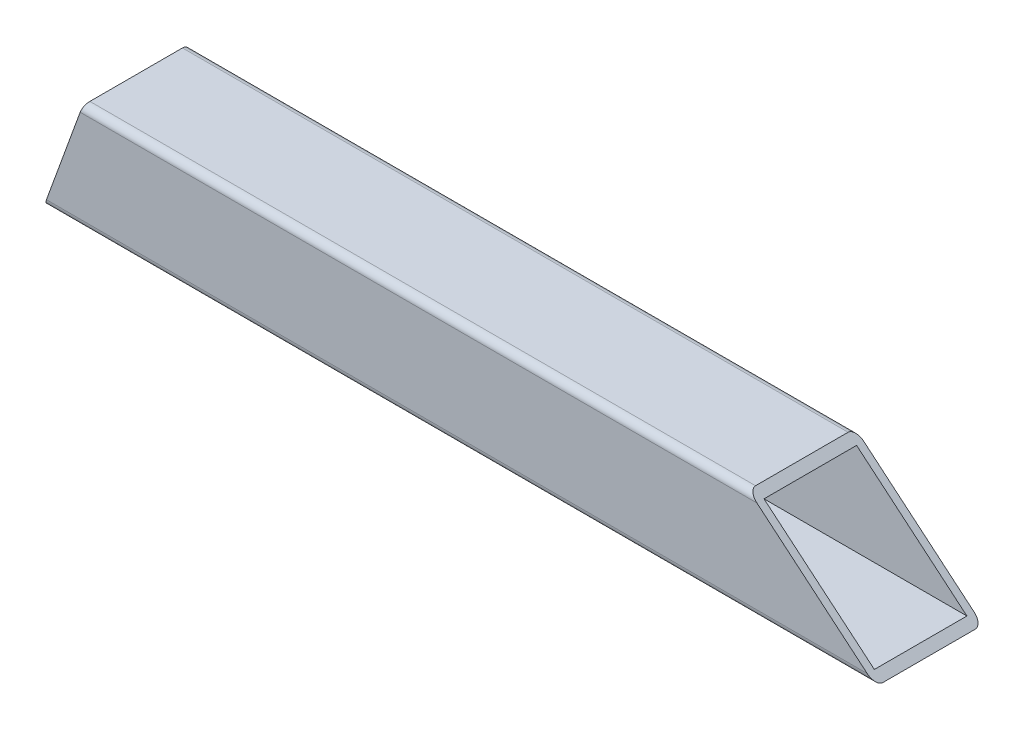
SolidWorks part; units mm, degrees
ref_plane "Front Plane" through (0, 0, 0) normal (0, 0, 1) x (1, 0, 0)
ref_plane "Top Plane" through (0, 0, 0) normal (0, 1, 0) x (1, 0, 0)
ref_plane "Right Plane" through (0, 0, 0) normal (1, 0, 0) x (0, 0, -1)
sketch "Sketch1" plane through (0, 0, 0) normal (1, 0, 0) x (0, 0, -1)
  line L0 (10, 10) -> (10, 140)
  line L1 (10, 0) -> (140, 0)
  line L2 (0, 10) -> (0, 140)
  line L3 (10, 150) -> (140, 150)
  line L4 (150, 10) -> (150, 140)
  line L5 (10, 10) -> (140, 10)
  line L6 (140, 10) -> (140, 140)
  line L7 (10, 140) -> (140, 140)
  arc A0 (0, 140) -> (10, 150) centre (10, 140) cw
  arc A1 (150, 140) -> (140, 150) centre (140, 140) ccw
  arc A2 (10, 0) -> (0, 10) centre (10, 10) cw
  arc A3 (140, 0) -> (150, 10) centre (140, 10) ccw
  point P6 (0, 150)
  point P9 (150, 150)
  point P12 (0, 0)
  dimension "D3" = 10
  dimension "Width" = 150
  dimension "D2" = 150
extrude "Extrude1" add sketch "Sketch1" along normal blind 1168
sketch "Sketch2" plane through (0, 0, 0) normal (0, 0, 1) x (1, 0, 0)
  line L0 (1168, 0) -> (989.237, 150)
  line L1 (1168, 150) -> (0, 150) construction
  line L3 (1168, 0) -> (0, 0) construction
  dimension "D1" = 40
extrude "Cut-Extrude1" cut sketch "Sketch2" against normal through all and the other way through all flip side to cut
sketch "Sketch3" plane through (0, 0, 0) normal (0, 0, 1) x (1, 0, 0)
  line L0 (0, 0) -> (54.5955, 150)
  line L1 (989.237, 150) -> (0, 150) construction
  line L2 (1168, 0) -> (0, 0) construction
  dimension "D1" = 70
extrude "Cut-Extrude2" cut sketch "Sketch3" against normal through all and the other way through all
